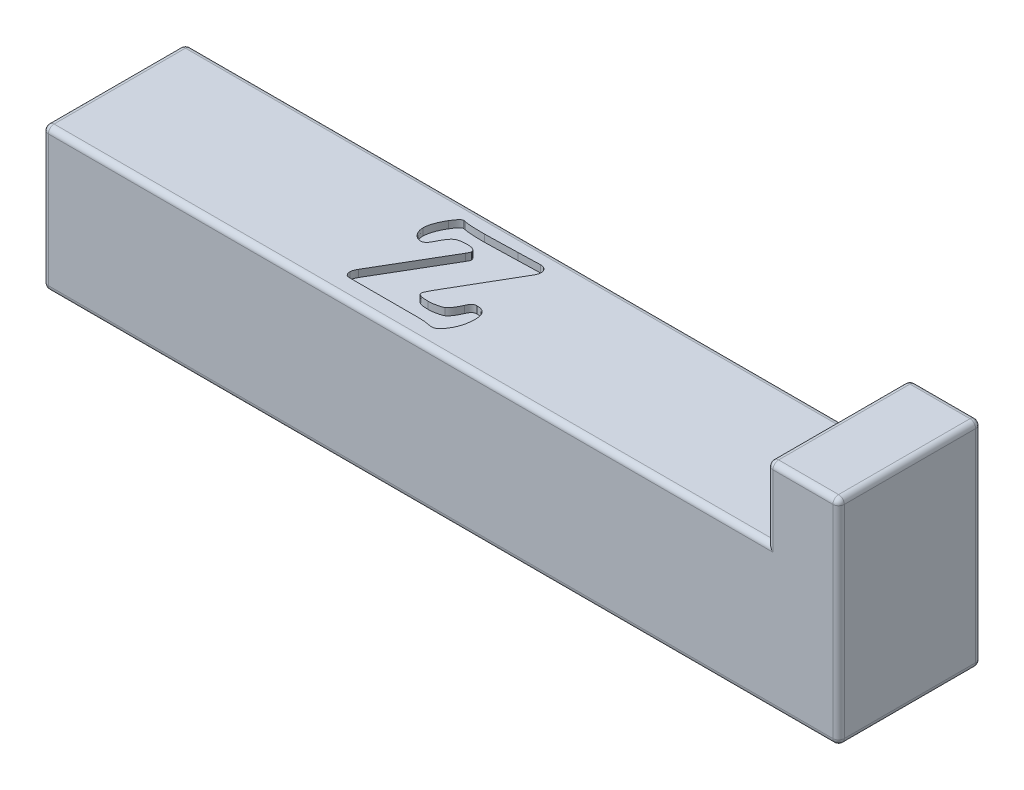
SolidWorks part; units mm, degrees
ref_plane "Front Plane" through (0, 0, 0) normal (0, 0, 1) x (1, 0, 0)
ref_plane "Top Plane" through (0, 0, 0) normal (0, 1, 0) x (1, 0, 0)
ref_plane "Right Plane" through (0, 0, 0) normal (1, 0, 0) x (0, 0, -1)
sketch "Sketch1" plane through (0, 0, 0) normal (0, 1, 0) x (1, 0, 0)
  line L1 (0, 0) -> (101.5, 0)
  line L2 (0, 0) -> (0, -20)
  line L3 (0, -20) -> (101.5, -20)
  line L4 (101.5, 0) -> (101.5, -20)
  dimension "D1" = 20
  dimension "D2" = 101.5
extrude "Boss-Extrude1" add sketch "Sketch1" along normal blind 20
sketch "Sketch2" plane through (101.5, 0, 0) normal (1, 0, 0) x (0, 0, -1)
  line L1 (-20, 0) -> (0, 0)
  line L2 (-20, 0) -> (-20, 30)
  line L3 (-20, 30) -> (0, 30)
  line L4 (0, 0) -> (0, 30)
  dimension "D1" = 30
extrude "Boss-Extrude2" add sketch "Sketch2" along normal blind 10
sketch "Sketch3" plane through (0, 20, 0) normal (0, 1, 0) x (1, 0, 0)
  text T0 "Z\r\n" font "Cooper Black" height in points 64
extrude "Cut-Extrude1" cut sketch "Sketch3" against normal blind 1
fillet "Fillet1" radius 0.8 17 edges at (111.5, 15, 0) (111.5, 30, 10) (106.5, 30, 0) (111.5, 15, 20) (111.5, 0, 10) (55.75, 0, 0) (106.5, 30, 20) (101.5, 30, 10) (101.5, 25, 0) (0, 0, 10) (55.75, 0, 20) (0, 10, 0) (101.5, 25, 20) (0, 10, 20) (0, 20, 10) (50.75, 20, 20) (50.75, 20, 0)
